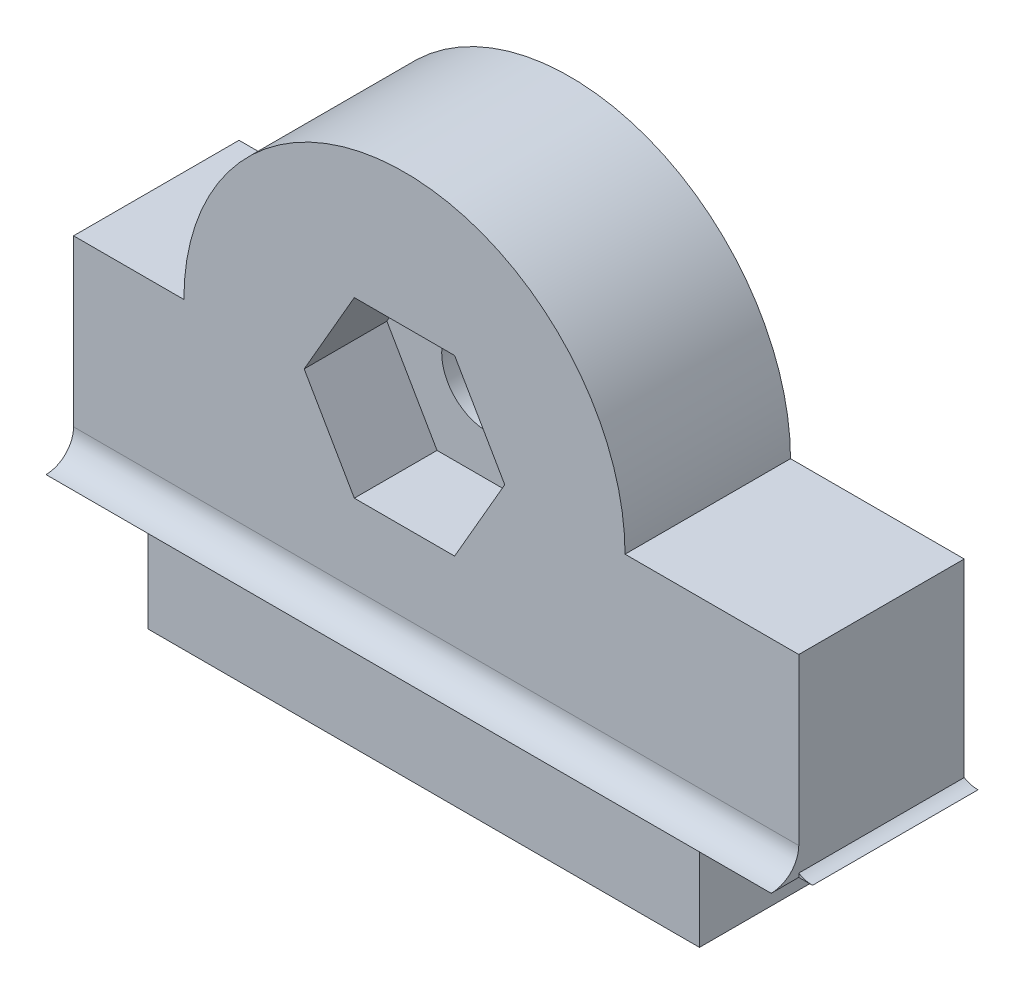
SolidWorks part; units mm, degrees
ref_plane "Front Plane" through (0, 0, 0) normal (0, 0, 1) x (1, 0, 0)
ref_plane "Top Plane" through (0, 0, 0) normal (0, 1, 0) x (1, 0, 0)
ref_plane "Right Plane" through (0, 0, 0) normal (1, 0, 0) x (0, 0, -1)
sketch "Sketch1" plane through (0, 0, 0) normal (0, 0, 1) x (1, 0, 0)
  line L0 (0, 0) -> (20, 0)
  line L1 (0, 0) -> (0, 4)
  line L2 (20, 0) -> (20, 4)
  line L3 (0, 4) -> (-2.7, 4)
  line L4 (23.6, 11) -> (23.6, 4)
  line L5 (-2.7, 4) -> (-2.7, 11)
  line L6 (-2.7, 11) -> (1.3, 11)
  line L7 (17.3, 11) -> (23.6, 11)
  line L8 (23.6, 4) -> (20, 4)
  line L11 (11.1187, 14.15) -> (7.4813, 14.15)
  line L12 (7.4813, 14.15) -> (5.6627, 11)
  line L13 (5.6627, 11) -> (7.4813, 7.85)
  line L14 (7.4813, 7.85) -> (11.1187, 7.85)
  line L15 (11.1187, 7.85) -> (12.9373, 11)
  line L16 (12.9373, 11) -> (11.1187, 14.15)
  arc A0 (17.3, 11) -> (1.3, 11) centre (9.3, 11) ccw
  circle A1 centre (9.3, 11) radius 3.15 construction
  point P19 (10, 0)
  dimension "D5" = 23.6
  dimension "D6" = 20
  dimension "D2" = 7
  dimension "D4" = 6.3
  dimension "D7" = 2.7
  dimension "D9" = 4
extrude "Boss-Extrude1" add sketch "Sketch1" along normal blind 6
sketch "Sketch2" plane through (-2.7, 0, 0) normal (-1, 0, 0) x (0, 0, 1)
  line L0 (3, 0) -> (3, 7) construction
  line L1 (6, 4) -> (6, 5)
  line L2 (6, 4) -> (7, 4)
  line L3 (0, 4) -> (-1, 4) construction
  line L4 (0, 4) -> (0, 5) construction
  arc A0 (6, 5) -> (7, 4) centre (7, 5) ccw
  arc A1 (0, 5) -> (-1, 4) centre (-1, 5) cw construction
  dimension "D1" = 1
  dimension "D2" = 1
  dimension "D3" = 6
  dimension "D4" = 3
  dimension "D5" = 4
extrude "Boss-Extrude2" add sketch "Sketch2" against normal up to surface (26.3 mm away) up to face at (23.6, 7.5, 3)
sketch "Sketch4" plane through (0, 0, 6) normal (0, 0, 1) x (1, 0, 0)
  line L0 (10.8, 0) -> (10.8, 7) construction
  line L1 (23.1, 4) -> (23.1, 5)
  line L2 (23.1, 4) -> (24.1, 4)
  line L3 (-1.5, 4) -> (-2.5, 4)
  line L4 (-1.5, 4) -> (-1.5, 5)
  arc A0 (23.1, 5) -> (24.1, 4) centre (24.1, 5) ccw
  arc A1 (-1.5, 5) -> (-2.5, 4) centre (-2.5, 5) cw
  dimension "D1" = 1
  dimension "D2" = 1
  dimension "D3" = 10.8
  dimension "D4" = 12.3
  dimension "D5" = 4
extrude "Boss-Extrude3" add sketch "Sketch4" against normal up to surface (6 mm away) up to face at (10.04, 6.8, 0)
sketch "Sketch8" plane through (0, 0, 6) normal (0, 0, 1) x (1, 0, 0)
  line L0 (5.6627, 11) -> (12.9373, 11) construction
  line L1 (11.1187, 14.15) -> (7.4813, 14.15) construction
  line L4 (7.4813, 14.15) -> (5.6627, 11)
  line L5 (5.6627, 11) -> (7.4813, 7.85)
  line L6 (7.4813, 7.85) -> (11.1187, 7.85)
  line L7 (11.1187, 7.85) -> (12.9373, 11)
  line L8 (12.9373, 11) -> (11.1187, 14.15)
  line L9 (11.1187, 14.15) -> (7.4813, 14.15)
  circle A0 centre (9.3, 11) radius 3.15 construction
  circle A1 centre (9.3, 11) radius 1.65
  point P4 (9.3, 11)
  point P6 (9.3, 7.85)
  point P14 (9.3, 14.15)
  dimension "D1" = 6.3
  dimension "D2" = 3.3
extrude "Boss-Extrude4" add sketch "Sketch8" against normal blind 3
sketch "Sketch9" plane through (0, 0, 0) normal (0, 0, -1) x (-1, 0, 0)
  line L1 (-11.1187, 14.15) -> (-12.9373, 11)
  line L2 (-12.9373, 11) -> (-11.1187, 7.85)
  line L3 (-11.1187, 7.85) -> (-7.4813, 7.85)
  line L4 (-7.4813, 7.85) -> (-5.6627, 11)
  line L5 (-5.6627, 11) -> (-7.4813, 14.15)
  line L6 (-7.4813, 14.15) -> (-11.1187, 14.15)
  circle A0 centre (-9.3, 11) radius 1.65
  circle A1 centre (-9.3, 11) radius 3.15 construction
  dimension "D1" = 3.3
  dimension "D2" = 6.3
sketch "Sketch11" plane through (0, 0, 6) normal (0, 0, 1) x (1, 0, 0)
  line L1 (7.4813, 14.15) -> (5.6627, 11)
  line L2 (5.6627, 11) -> (7.4813, 7.85)
  line L3 (7.4813, 7.85) -> (11.1187, 7.85)
  line L4 (11.1187, 7.85) -> (12.9373, 11)
  line L5 (12.9373, 11) -> (11.1187, 14.15)
  line L6 (11.1187, 14.15) -> (7.4813, 14.15)
  circle A1 centre (9.3, 11) radius 3.15 construction
  dimension "D1" = 6.3
extrude "Cut-Extrude1" cut sketch "Sketch11" against normal blind 10
extrude "Boss-Extrude5" add sketch "Sketch9" against normal blind 3
equation "\"D4@Sketch1\" = 6 + \"tol1@parametersSketch@prostheticParameters.SLDPRT\""
equation "\"D1@Sketch8\"= 6 + \"tol1@parametersSketch@prostheticParameters.SLDPRT\""
equation "\"D2@Sketch8\"= 3 + \"tol1@parametersSketch@prostheticParameters.SLDPRT\""
equation "\"D1@Sketch9\"= 3 + \"tol1@parametersSketch@prostheticParameters.SLDPRT\""
equation "\"D2@Sketch9\"= 6 + \"tol1@parametersSketch@prostheticParameters.SLDPRT\""
equation "\"D1@Sketch11\"= 6 + \"tol1@parametersSketch@prostheticParameters.SLDPRT\""
